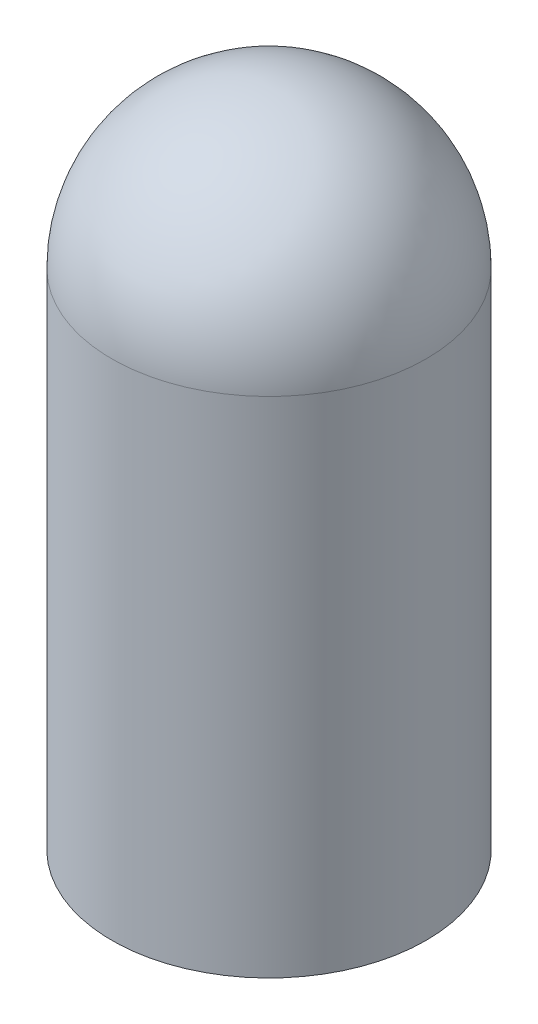
SolidWorks part; units mm, degrees
ref_plane "Front Plane" through (0, 0, 0) normal (0, 0, 1) x (1, 0, 0)
ref_plane "Top Plane" through (0, 0, 0) normal (0, 1, 0) x (1, 0, 0)
ref_plane "Right Plane" through (0, 0, 0) normal (1, 0, 0) x (0, 0, -1)
sketch "Sketch1" plane through (0, 0, 0) normal (0, 0, 1) x (1, 0, 0)
  line L0 (9.75, 0) -> (9.75, 31.25)
  line L1 (0, 0) -> (9.75, 0)
  line L2 (0, 41) -> (0, 0)
  arc A0 (9.75, 31.25) -> (0, 41) centre (0, 31.25) ccw
  dimension "D1" = 31.25
  dimension "D2" = 9.75
revolve "Revolve1" add sketch "Sketch1" angle 360 about L2
shell "Shell1" thickness 0.5
